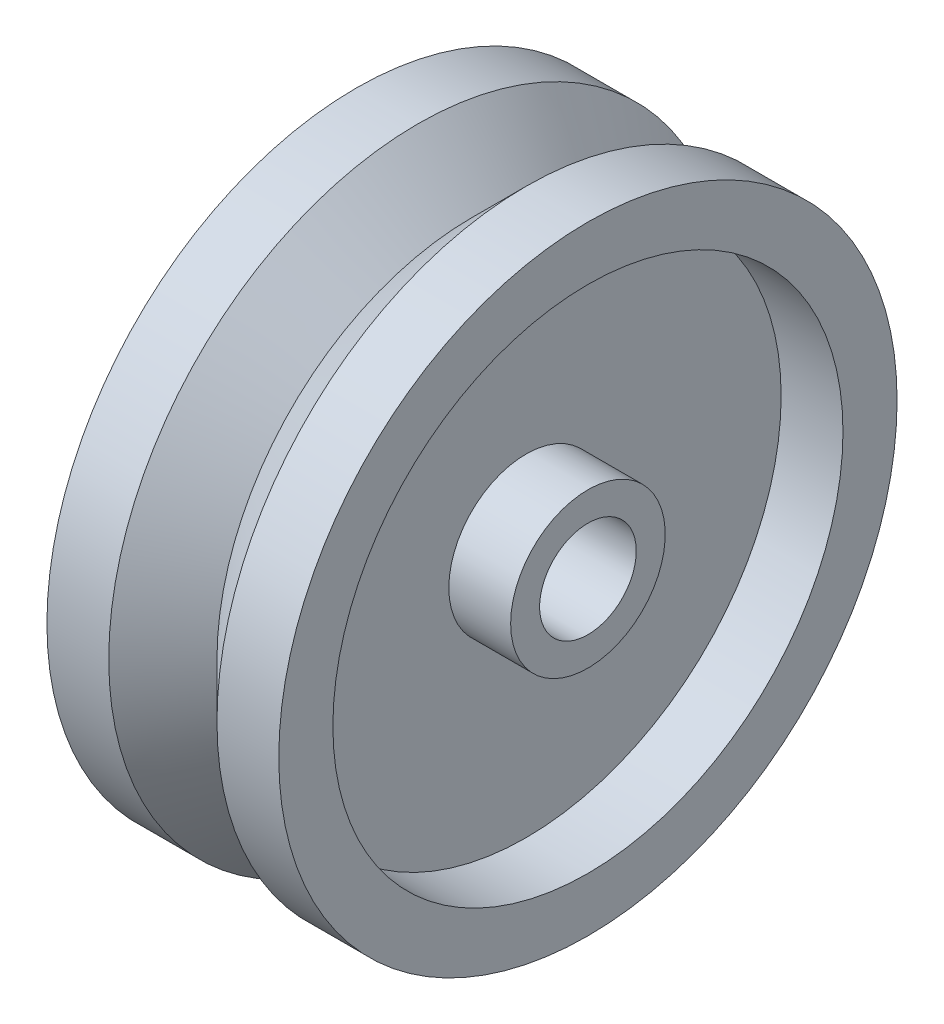
SolidWorks part; units mm, degrees
ref_plane "Front Plane" through (0, 0, 0) normal (0, 0, 1) x (1, 0, 0)
ref_plane "Top Plane" through (0, 0, 0) normal (0, 1, 0) x (1, 0, 0)
ref_plane "Right Plane" through (0, 0, 0) normal (1, 0, 0) x (0, 0, -1)
sketch "Sketch1" plane through (0, 0, 0) normal (1, 0, 0) x (0, 0, -1)
  circle A0 centre (0, 0) radius 20
  circle A1 centre (0, 0) radius 3.125
  dimension "D1" = 40
  dimension "D2" = 6.25
extrude "Boss-Extrude1" add sketch "Sketch1" along normal mid plane 15
sketch "Sketch2" plane through (7.5, 0, 0) normal (1, 0, 0) x (0, 0, -1)
  circle A0 centre (0, 0) radius 16.5
  circle A1 centre (0, 0) radius 5
  dimension "D1" = 33
  dimension "D2" = 10
extrude "Cut-Extrude1" cut sketch "Sketch2" against normal blind 4 and the other way through all
mirror "Mirror1" about plane through (0, 0, 0) normal (1, 0, 0) of "Cut-Extrude1"
sketch "Sketch3" plane through (0, 0, 0) normal (0, 0, 1) x (1, 0, 0)
  line L0 (-3.5, 20) -> (0, 16.5)
  line L1 (0, 16.5) -> (3.5, 20)
  line L2 (7.5, 20) -> (-7.5, 20) construction
  line L3 (0, 0) -> (0, 7.0803) construction
  line L4 (-7.5, 20) -> (-7.5, -20) construction
  line L5 (-3.5, 20) -> (3.5, 20)
  line L7 (0, 0) -> (12.2648, 0) construction
  dimension "D1" = 90
  dimension "D2" = 4
revolve "Cut-Revolve2" cut sketch "Sketch3" angle 360 about L7
